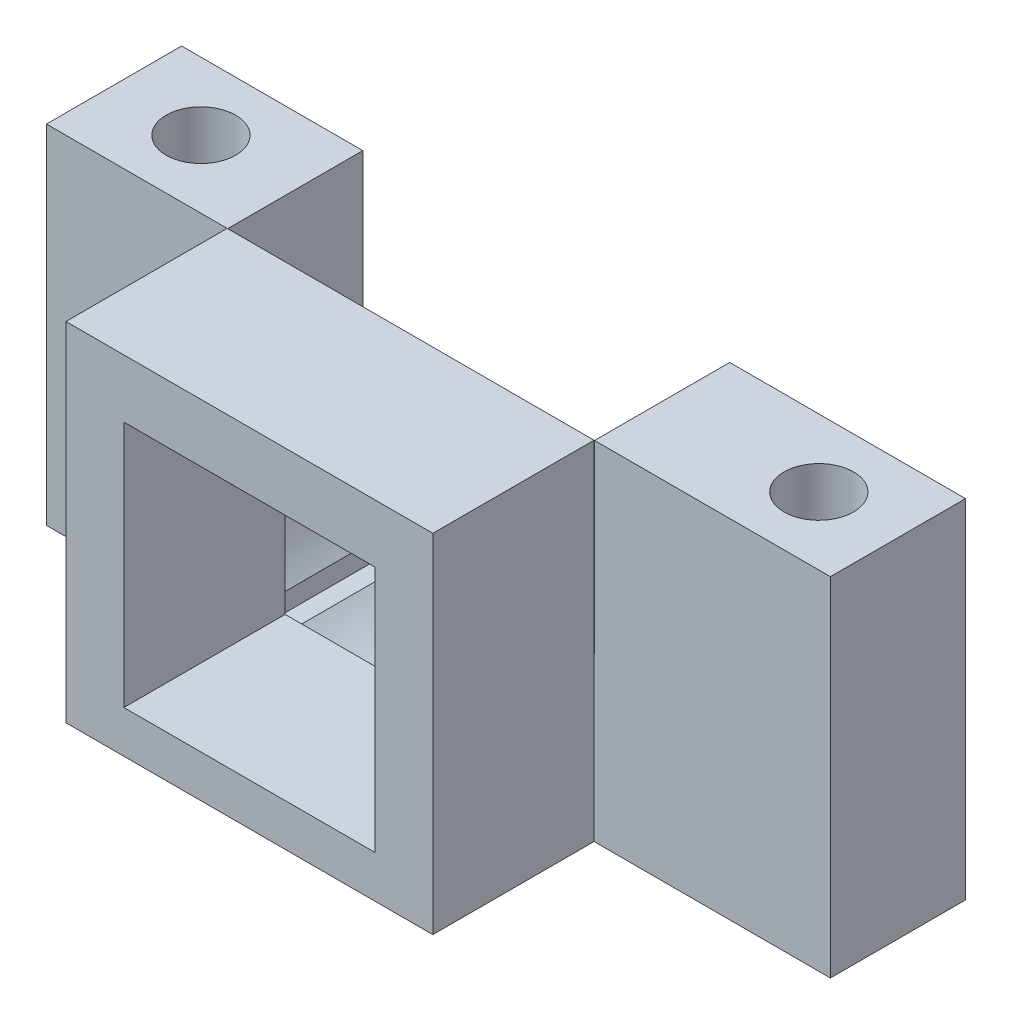
SolidWorks part; units mm, degrees
ref_plane "Front Plane" through (0, 0, 0) normal (0, 0, 1) x (1, 0, 0)
ref_plane "Top Plane" through (0, 0, 0) normal (0, 1, 0) x (1, 0, 0)
ref_plane "Right Plane" through (0, 0, 0) normal (1, 0, 0) x (0, 0, -1)
sketch "Sketch1" plane through (0, 0, 0) normal (0, 0, 1) x (1, 0, 0)
  line L0 (-0.5, 1.7) -> (40.1, 1.7)
  line L12 (8.8843, 20.0309) -> (27.8843, 20.0309)
  line L13 (8.8843, 20.0309) -> (8.8843, 10.1196)
  line L14 (8.8843, 10.1196) -> (27.8843, 10.1196)
  line L15 (27.8843, 20.0309) -> (27.8843, 10.1196)
  line L16 (-0.5, 19.7) -> (40.1, 19.7)
  line L17 (-0.5, 19.7) -> (-0.5, 1.7)
  line L18 (40.1, 19.7) -> (40.1, 1.7)
  line L19 (11.6843, 16.9357) -> (25.0843, 16.9357)
  line L20 (11.6843, 16.9357) -> (11.6843, 3.7857)
  line L21 (11.6843, 3.7857) -> (25.0843, 3.7857)
  line L22 (25.0843, 16.9357) -> (25.0843, 3.7857)
  circle A1 centre (18.3887, 10.3631) radius 8.75
extrude "Boss-Extrude1" add sketch "Sketch1" along normal blind 7 contours A1 L14 L13 L16 L17 L0 L21 L20 | A1 L0 L18 L16 L15 L14 L22 L21
sketch "Sketch2" plane through (0, 0, 7) normal (0, 0, 1) x (1, 0, 0)
  line L0 (8.86, 19.7) -> (27.8604, 19.7)
  line L1 (8.86, 19.7) -> (8.86, 1.7)
  line L2 (8.86, 1.7) -> (27.8604, 1.7)
  line L3 (27.8604, 19.7) -> (27.8604, 1.7)
  line L4 (11.8604, 16.6875) -> (24.8604, 16.6875)
  line L5 (11.8604, 16.6875) -> (11.8604, 3.8875)
  line L6 (11.8604, 3.8875) -> (24.8604, 3.8875)
  line L7 (24.8604, 16.6875) -> (24.8604, 3.8875)
extrude "Boss-Extrude2" add sketch "Sketch2" along normal blind 8.35
sketch "Sketch3" plane through (0, 19.7, 0) normal (0, 1, 0) x (1, 0, 0)
  circle A0 centre (4, -3.5) radius 1.8
  circle A1 centre (36, -3.5) radius 1.8
extrude "Cut-Extrude1" cut sketch "Sketch3" against normal through all
